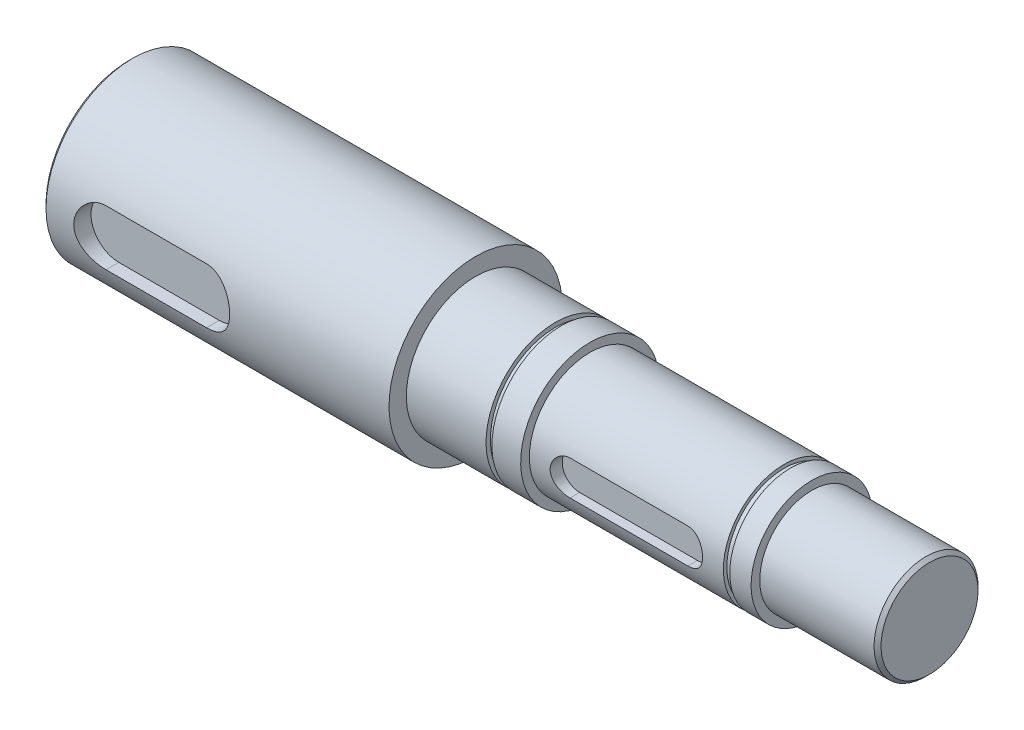
SolidWorks part; units mm, degrees
ref_plane "前视基准面" through (0, 0, 0) normal (0, 0, 1) x (1, 0, 0)
ref_plane "上视基准面" through (0, 0, 0) normal (0, 1, 0) x (1, 0, 0)
ref_plane "右视基准面" through (0, 0, 0) normal (1, 0, 0) x (0, 0, -1)
sketch "草图1" plane through (0, 0, 0) normal (0, 0, 1) x (1, 0, 0)
  line L0 (0, 0) -> (0, 25)
  line L1 (0, -55) -> (0, 55) construction
  line L2 (0, 25) -> (100, 25)
  line L3 (100, 25) -> (100, 20)
  line L4 (100, 20) -> (133, 20)
  line L5 (133, 20) -> (133, 17.5)
  line L6 (133, 17.5) -> (197, 17.5)
  line L7 (197, 17.5) -> (197, 15)
  line L8 (197, 15) -> (231, 15)
  line L9 (231, 15) -> (231, 0)
  line L10 (231, 0) -> (0, 0) construction
  line L11 (0, 0) -> (231, 0)
  dimension "D1" = 50
  dimension "D2" = 40
  dimension "D3" = 35
  dimension "D4" = 30
  dimension "D5" = 231
  dimension "D6" = 64
  dimension "D7" = 33
  dimension "D8" = 100
revolve "旋转1" add sketch "草图1" angle 360 about L10
chamfer "倒角1" distance 1 angle 45 2 edges at (0, 25, 0) (231, 15, 0)
sketch "草图2" plane through (197, 0, 0) normal (1, 0, 0) x (0, 0, -1)
  circle A2 centre (0, 0) radius 16.5
  circle A3 centre (0, 0) radius 16.5
  dimension "D1" = 1
extrude "切除-拉伸1" cut sketch "草图2" along normal blind 1.85 from offset 8 flip side to cut offset against normal yes
sketch "草图3" plane through (133, 0, 0) normal (1, 0, 0) x (0, 0, -1)
  circle A2 centre (0, 0) radius 18.75
  circle A3 centre (0, 0) radius 18.75
  dimension "D1" = 1.25
extrude "切除-拉伸2" cut sketch "草图3" along normal blind 1.7 from offset 10 flip side to cut offset against normal yes
sketch "草图4" plane through (0, 0, 0) normal (0, 0, 1) x (1, 0, 0)
  line L0 (17, 0) -> (46, 0) construction
  line L1 (27.5, 0) -> (-27.5, 0) construction
  line L2 (17, 8) -> (46, 8)
  line L3 (17, -8) -> (46, -8)
  arc A0 (17, 8) -> (17, -8) centre (17, 0) ccw
  arc A1 (46, -8) -> (46, 8) centre (46, 0) ccw
  point P5 (31.5, 0)
  dimension "D2" = 45
  dimension "D3" = 9
  dimension "D1" = 16
extrude "切除-拉伸3" cut sketch "草图4" along normal through all from offset 20
sketch "草图5" plane through (0, 0, 0) normal (0, 0, 1) x (1, 0, 0)
  line L0 (144, 0) -> (178, 0) construction
  line L1 (144, 5) -> (178, 5)
  line L2 (144, -5) -> (178, -5)
  line L9 (133, -17.5) -> (133, 17.5) construction
  arc A0 (144, 5) -> (144, -5) centre (144, 0) ccw
  arc A1 (178, -5) -> (178, 5) centre (178, 0) ccw
  point P3 (161, 0)
  point P12 (139, 0)
  dimension "D2" = 44
  dimension "D3" = 6
  dimension "D1" = 10
extrude "切除-拉伸4" cut sketch "草图5" along normal through all from offset 14
